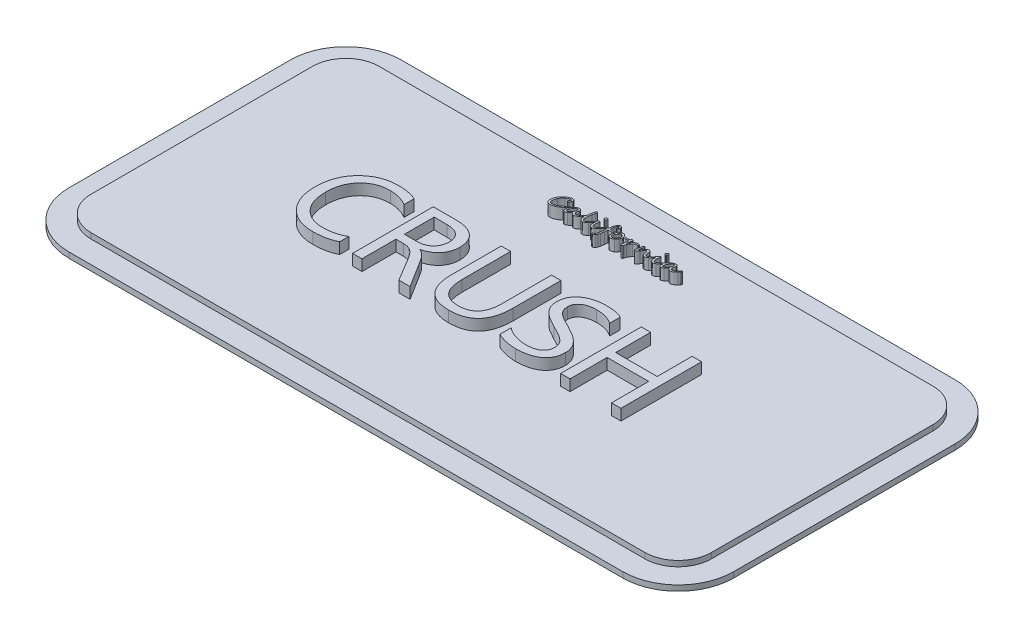
SolidWorks part; units mm, degrees
ref_plane "Front Plane" through (0, 0, 0) normal (0, 0, 1) x (1, 0, 0)
ref_plane "Top Plane" through (0, 0, 0) normal (0, 1, 0) x (1, 0, 0)
ref_plane "Right Plane" through (0, 0, 0) normal (1, 0, 0) x (0, 0, -1)
sketch "Sketch1" plane through (0, 0, 0) normal (0, 1, 0) x (1, 0, 0)
  line L1 (-76.2, -38.1) -> (76.2, -38.1)
  line L2 (-76.2, -38.1) -> (-76.2, 38.1)
  line L3 (-76.2, 38.1) -> (76.2, 38.1)
  line L4 (76.2, -38.1) -> (76.2, 38.1)
  line L5 (-76.2, -38.1) -> (76.2, 38.1) construction
  line L6 (-76.2, 38.1) -> (76.2, -38.1) construction
  point P0 (0, 0)
  dimension "D1" = 76.2
  dimension "D2" = 152.4
extrude "Boss-Extrude1" add sketch "Sketch1" along normal blind 2.54
fillet "Fillet1" radius 12.7 4 edges at (76.2, 1.27, -38.1) (76.2, 1.27, 38.1) (-76.2, 1.27, 38.1) (-76.2, 1.27, -38.1)
sketch "Sketch3" plane through (0, 2.54, 0) normal (0, 1, 0) x (1, 0, 0)
  text T1 "CRUSH" font "Yu Gothic UI" height in points 72
sketch "Sketch4" plane through (0, 2.54, 0) normal (0, 1, 0) x (1, 0, 0)
  line L4 (-76.2, 25.4) -> (-76.2, -25.4)
  line L5 (-63.5, -38.1) -> (63.5, -38.1)
  line L6 (76.2, -25.4) -> (76.2, 25.4)
  line L7 (63.5, 38.1) -> (-63.5, 38.1)
  line L8 (-71.12, 25.4) -> (-71.12, -25.4)
  line L9 (-63.5, -33.02) -> (63.5, -33.02)
  line L10 (71.12, -25.4) -> (71.12, 25.4)
  line L11 (63.5, 33.02) -> (-63.5, 33.02)
  line L12 (-71.12, 25.4) -> (-71.12, -25.4)
  line L13 (-63.5, -33.02) -> (63.5, -33.02)
  line L14 (71.12, -25.4) -> (71.12, 25.4)
  line L15 (63.5, 33.02) -> (-63.5, 33.02)
  arc A4 (-63.5, 38.1) -> (-76.2, 25.4) centre (-63.5, 25.4) ccw
  arc A5 (-76.2, -25.4) -> (-63.5, -38.1) centre (-63.5, -25.4) ccw
  arc A6 (63.5, -38.1) -> (76.2, -25.4) centre (63.5, -25.4) ccw
  arc A7 (76.2, 25.4) -> (63.5, 38.1) centre (63.5, 25.4) ccw
  arc A8 (-63.5, 33.02) -> (-71.12, 25.4) centre (-63.5, 25.4) ccw
  arc A9 (-71.12, -25.4) -> (-63.5, -33.02) centre (-63.5, -25.4) ccw
  arc A10 (63.5, -33.02) -> (71.12, -25.4) centre (63.5, -25.4) ccw
  arc A11 (71.12, 25.4) -> (63.5, 33.02) centre (63.5, 25.4) ccw
  arc A12 (-63.5, 33.02) -> (-71.12, 25.4) centre (-63.5, 25.4) ccw
  arc A13 (-71.12, -25.4) -> (-63.5, -33.02) centre (-63.5, -25.4) ccw
  arc A14 (63.5, -33.02) -> (71.12, -25.4) centre (63.5, -25.4) ccw
  arc A15 (71.12, 25.4) -> (63.5, 33.02) centre (63.5, 25.4) ccw
  dimension "D1" = 5.08
  dimension "D2" = 5.08
extrude "Cut-Extrude2" cut sketch "Sketch4" against normal blind 1.27
extrude "Boss-Extrude2" add sketch "Sketch3" along normal blind 2.54
sketch "Sketch5" plane through (0, 2.54, 0) normal (0, 1, 0) x (1, 0, 0)
  line L0 (-15.24, 22.86) -> (-15.24, -33.02) construction
  line L1 (-63.5, -33.02) -> (63.5, -33.02) construction
  line L2 (-15.24, 22.86) -> (-71.12, 22.86) construction
  line L3 (-71.12, 25.4) -> (-71.12, -25.4) construction
  text T0 "California" font "Segoe Script" height 3.5
  dimension "D1" = 55.88
  dimension "D2" = 55.88
extrude "Boss-Extrude3" add sketch "Sketch5" along normal blind 2.54
